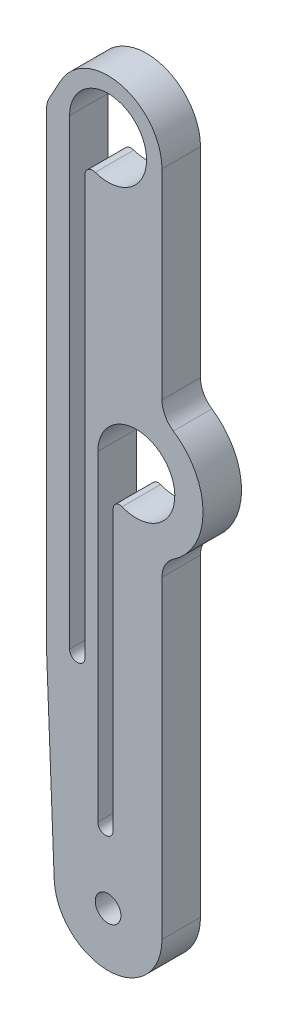
SolidWorks part; units mm, degrees
ref_plane "前视基准面" through (0, 0, 0) normal (0, 0, 1) x (1, 0, 0)
ref_plane "上视基准面" through (0, 0, 0) normal (0, 1, 0) x (1, 0, 0)
ref_plane "右视基准面" through (0, 0, 0) normal (1, 0, 0) x (0, 0, -1)
sketch "草图1" plane through (0, 0, 0) normal (0, 0, 1) x (1, 0, 0)
  line L0 (-1.8, 15.6) -> (-1.8, 48.2059)
  line L1 (-3, 51.6) -> (-3, 15.6)
  line L4 (-4.8017, 51.135) -> (-4.8017, 14.8455)
  line L9 (4.2, -0.4) -> (4.2, 3)
  line L13 (4.2, 47.4) -> (4.2, 51.6)
  line L14 (-3.7053, 53.5775) -> (-4.5748, 52.0068)
  line L15 (4.2, 47.4) -> (4.2, 36.02)
  line L16 (4.2, 24.0467) -> (4.2, 3)
  line L17 (-0.8, 30.0334) -> (-0.8, 5.0334)
  line L19 (0.4, 5.0334) -> (0.4, 26.7837)
  line L21 (-4.8017, 14.8455) -> (-4.1968, -0.5648)
  circle A0 centre (0, -0.4) radius 1
  circle A1 centre (1.2, 30.0334) radius 1 construction
  arc A2 (-1, 48.7716) -> (-1.8, 48.2059) centre (-1.2, 48.2059) ccw
  arc A3 (-1, 48.7716) -> (-3, 51.6) centre (0, 51.6) ccw
  arc A4 (-3, 15.6) -> (-1.8, 15.6) centre (-2.4, 15.6) ccw
  arc A25 (4.2, 51.6) -> (-3.7053, 53.5775) centre (0, 51.6) ccw
  arc A26 (-4.5748, 52.0068) -> (-4.8017, 51.135) centre (-3.0017, 51.1319) ccw
  arc A27 (1.0857, 27.248) -> (-0.8, 30.0334) centre (2.2, 30.0334) ccw
  arc A29 (5.0889, 25.7097) -> (5.0889, 34.3571) centre (2.2, 30.0334) ccw
  arc A30 (4.2, 24.0467) -> (5.0889, 25.7097) centre (6.2, 24.0467) cw
  arc A31 (4.2, 36.02) -> (5.0889, 34.3571) centre (6.2, 36.02) ccw
  arc A32 (0.4, 26.7837) -> (1.0857, 27.248) centre (0.9, 26.7837) cw
  arc A33 (-0.8, 5.0334) -> (0.4, 5.0334) centre (-0.2, 5.0334) ccw
  arc A34 (-4.1968, -0.5648) -> (4.2, -0.4) centre (0, -0.4) ccw
  dimension "D2" = 3
  dimension "D3" = 2
  dimension "D6" = 2
  dimension "D8" = 3
  dimension "D9" = 6
  dimension "D10" = 25
  dimension "D12" = 2
  dimension "D13" = 0.5
  dimension "D1" = 52
  dimension "D4" = 1.2
  dimension "D5" = 36
  dimension "D7" = 21.6
  dimension "D11" = 1.2
extrude "凸台-拉伸1" add sketch "草图1" along normal blind 3
